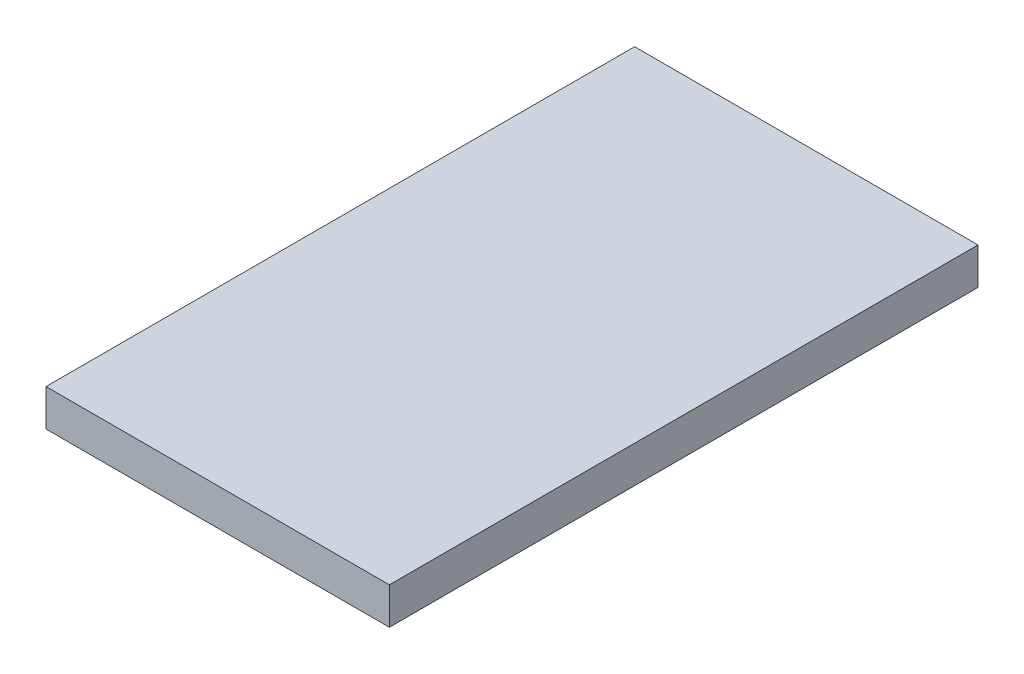
SolidWorks part; units mm, degrees
ref_plane "Front Plane" through (0, 0, 0) normal (0, 0, 1) x (1, 0, 0)
ref_plane "Top Plane" through (0, 0, 0) normal (0, 1, 0) x (1, 0, 0)
ref_plane "Right Plane" through (0, 0, 0) normal (1, 0, 0) x (0, 0, -1)
sketch "Sketch1" plane through (0, 0, 0) normal (0, 1, 0) x (1, 0, 0)
  line L1 (-88.9, -152.4) -> (88.9, -152.4)
  line L2 (-88.9, -152.4) -> (-88.9, 152.4)
  line L3 (-88.9, 152.4) -> (88.9, 152.4)
  line L4 (88.9, -152.4) -> (88.9, 152.4)
  line L5 (-88.9, -152.4) -> (88.9, 152.4) construction
  line L6 (-88.9, 152.4) -> (88.9, -152.4) construction
  point P0 (0, 0)
  dimension "D1" = 177.8
  dimension "D2" = 304.8
extrude "Boss-Extrude1" add sketch "Sketch1" along normal mid plane 19.05
